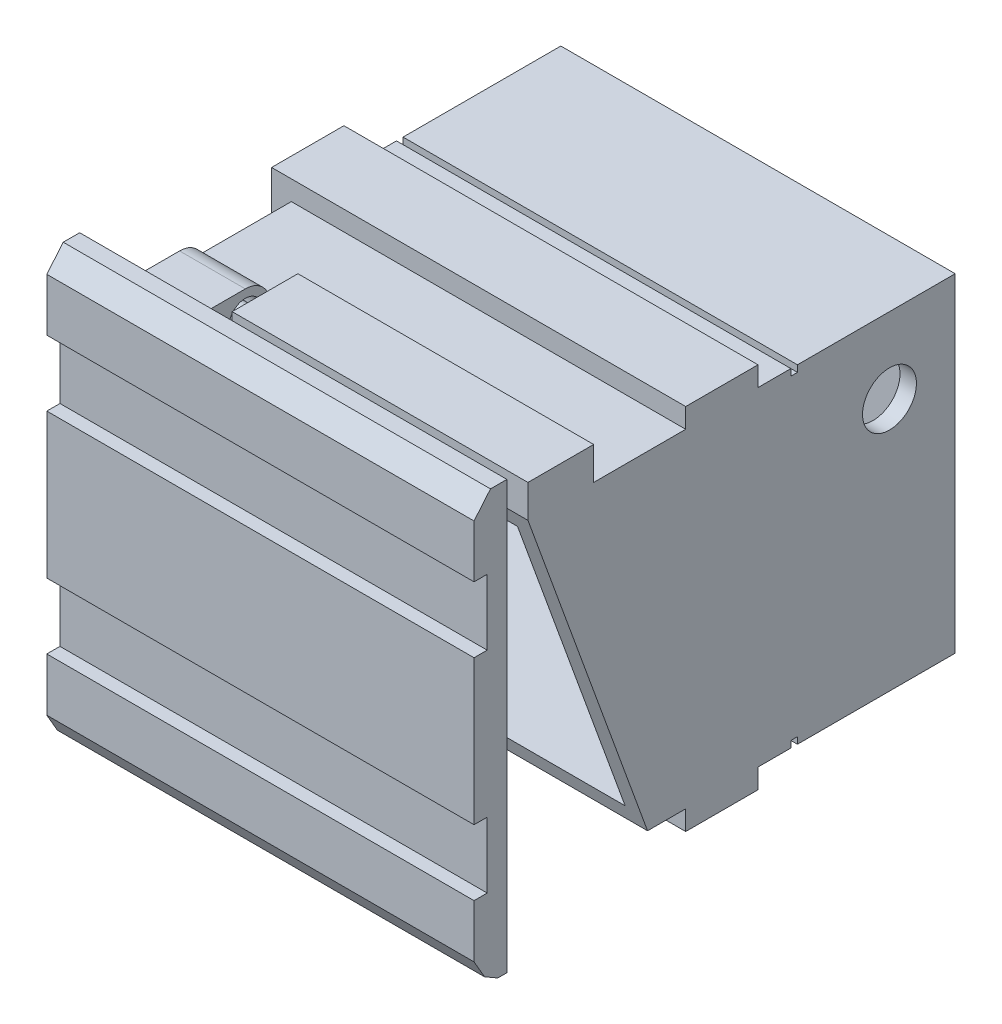
SolidWorks part; units mm, degrees
ref_plane "Alzado" through (0, 0, 0) normal (0, 0, 1) x (1, 0, 0)
ref_plane "Planta" through (0, 0, 0) normal (0, 1, 0) x (1, 0, 0)
ref_plane "Vista lateral" through (0, 0, 0) normal (1, 0, 0) x (0, 0, -1)
sketch "Croquis2" plane through (0, 0, 0) normal (0, 0, 1) x (1, 0, 0)
  line L1 (-30, 25) -> (30, 25)
  line L2 (-30, 25) -> (-30, -25)
  line L3 (-30, -25) -> (30, -25)
  line L4 (30, 25) -> (30, -25)
  line L5 (-30, 25) -> (30, -25) construction
  line L6 (-30, -25) -> (30, 25) construction
  point P0 (0, 0)
  dimension "D1" = 60
  dimension "D2" = 50
extrude "Saliente-Extruir2" add sketch "Croquis2" along normal blind 5
sketch "Croquis3" plane through (0, 0, 5) normal (0, 0, 1) x (1, 0, 0)
  line L1 (-27.5, 22.5) -> (27.5, 22.5)
  line L2 (-27.5, 22.5) -> (-27.5, -22.5)
  line L3 (-27.5, -22.5) -> (27.5, -22.5)
  line L4 (27.5, 22.5) -> (27.5, -22.5)
  line L5 (-27.5, 22.5) -> (27.5, -22.5) construction
  line L6 (-27.5, -22.5) -> (27.5, 22.5) construction
  line L7 (30, -25) -> (-30, -25)
  line L8 (30, -25) -> (30, 25)
  line L9 (30, 25) -> (-30, 25)
  line L10 (-30, -25) -> (-30, 25)
  point P0 (0, 0)
  dimension "D1" = 55
  dimension "D2" = 45
extrude "Saliente-Extruir3" add sketch "Croquis3" along normal blind 60
sketch "Croquis4" plane through (30, 0, 0) normal (1, 0, 0) x (0, 0, -1)
  line L0 (0, -25) -> (0, 25) construction
  line L2 (-65, 25) -> (0, 25) construction
  line L3 (-5, 22.5) -> (-15, 22.5)
  line L4 (-5, 22.5) -> (-5, 8.5)
  line L5 (-5, 8.5) -> (-15, 8.5)
  line L6 (-15, 22.5) -> (-15, 8.5)
  circle A1 centre (-10, 13.5) radius 4.1
  dimension "D1" = 14
  dimension "D2" = 5
  dimension "D3" = 8.2
  dimension "D4" = 5
  dimension "D5" = 5
  dimension "D6" = 2.5
  dimension "D7" = 10
extrude "Cortar-Extruir2" cut sketch "Croquis4" against normal blind 5 contours A1
sketch "Croquis5" plane through (30, 0, 0) normal (1, 0, 0) x (0, 0, -1)
  line L0 (-65, 25) -> (-46.8015, -25)
  line L1 (-65, -25) -> (0, -25) construction
  line L2 (-65, -25) -> (-65, 25) construction
  line L3 (-46.8015, -25) -> (-65, -25)
  line L4 (-65, -25) -> (-65, 25)
  dimension "D1" = 20
extrude "Cortar-Extruir3" cut sketch "Croquis5" against normal through all
sketch "Croquis18" plane through (-30, 0, 0) normal (-1, 0, 0) x (0, 0, 1)
  line L0 (65, 25) -> (0, 25) construction
  line L1 (46.8015, -25) -> (0, -25) construction
  line L2 (30, 25) -> (41, 25)
  line L3 (30, 25) -> (30, -25)
  line L4 (30, -25) -> (41, -25)
  line L5 (41, 25) -> (41, -25)
  line L6 (0, 25) -> (0, -25) construction
  dimension "D1" = 30
  dimension "11" = 11
extrude "Saliente-Extruir10" add sketch "Croquis18" along normal blind 3
sketch "Croquis19" plane through (0, -25, 0) normal (0, -1, 0) x (1, 0, 0)
  line L0 (30, 46.8015) -> (30, 0) construction
  line L2 (-33, 41) -> (30, 41)
  line L3 (-33, 41) -> (-33, 30)
  line L4 (-33, 30) -> (30, 30)
  line L5 (30, 41) -> (30, 30)
  dimension "D1" = 11
extrude "Saliente-Extruir11" add sketch "Croquis19" along normal blind 3
sketch "Croquis20" plane through (0, 25, 0) normal (0, 1, 0) x (1, 0, 0)
  line L1 (-33, -41) -> (30, -41)
  line L2 (-33, -41) -> (-33, -30)
  line L3 (-33, -30) -> (30, -30)
  line L4 (30, -41) -> (30, -30)
extrude "Saliente-Extruir12" add sketch "Croquis20" along normal blind 3
sketch "Croquis21" plane through (30, 0, 0) normal (1, 0, 0) x (0, 0, -1)
  line L0 (-30, -25) -> (0, -25) construction
  line L1 (-25, -25) -> (-24, -25)
  line L2 (-25, -25) -> (-25, -24)
  line L3 (-25, -24) -> (-24, -24)
  line L4 (-24, -25) -> (-24, -24)
  line L5 (-30, -28) -> (-30, -25) construction
  dimension "D1" = 5
  dimension "D2" = 1
  dimension "1" = 1
extrude "Cortar-Extruir8" cut sketch "Croquis21" against normal blind 65
sketch "Croquis23" plane through (30, 0, 0) normal (1, 0, 0) x (0, 0, -1)
  line L0 (-30, 25) -> (0, 25) construction
  line L1 (-25, 25) -> (-24, 25)
  line L2 (-25, 25) -> (-25, 24)
  line L3 (-25, 24) -> (-24, 24)
  line L4 (-24, 25) -> (-24, 24)
  line L5 (-30, 28) -> (-30, 25) construction
  dimension "D1" = 5
  dimension "D2" = 1
  dimension "D3" = 1
extrude "Cortar-Extruir10" cut sketch "Croquis23" against normal blind 65
sketch "Croquis22" plane through (0, 25, 0) normal (0, 1, 0) x (1, 0, 0)
  line L0 (-30, -30) -> (-30, -25) construction
  line L1 (-30, -25) -> (-29, -25)
  line L2 (-30, -25) -> (-30, -24)
  line L3 (-30, -24) -> (-29, -24)
  line L4 (-29, -25) -> (-29, -24)
  line L5 (30, -30) -> (-30, -30) construction
  dimension "D1" = 1
  dimension "D2" = 1
  dimension "5" = 5
extrude "Cortar-Extruir9" cut sketch "Croquis22" against normal blind 65
sketch "Croquis29" plane through (0, 25, 0) normal (0, 1, 0) x (1, 0, 0)
  line L0 (30, -65) -> (30, -41) construction
  line L1 (30, -55) -> (-15, -55)
  line L2 (30, -55) -> (30, -65)
  line L3 (30, -65) -> (-15, -65)
  line L4 (-15, -55) -> (-15, -65)
  line L5 (30, -65) -> (-30, -65) construction
  dimension "D1" = 45
  dimension "D2" = 10
extrude "Saliente-Extruir13" add sketch "Croquis29" along normal blind 5
sketch "Croquis30" plane through (0, 25, 0) normal (0, 1, 0) x (1, 0, 0)
  line L0 (-15, -65) -> (-30, -65) construction
  line L1 (-15, -55) -> (-27.5, -55)
  line L2 (-15, -55) -> (-15, -65)
  line L3 (-15, -65) -> (-27.5, -65)
  line L4 (-27.5, -55) -> (-27.5, -65)
  line L5 (-30, -65) -> (-30, -41) construction
  dimension "D1" = 2.5
extrude "Cortar-Extruir11" cut sketch "Croquis30" against normal blind 3
sketch "Croquis31" plane through (-15, 0, 0) normal (-1, 0, 0) x (0, 0, 1)
  line L0 (55, 30) -> (65, 30) construction
  line L2 (55, 30) -> (55, 25) construction
  circle A0 centre (61, 26.25) radius 1.5
  dimension "D2" = 3
  dimension "D1" = 3.75
  dimension "D3" = 6
extrude "Saliente-Extruir14" add sketch "Croquis31" along normal blind 11.5
sketch "Croquis32" plane through (-15, 0, 0) normal (-1, 0, 0) x (0, 0, 1)
  line L0 (61, 30) -> (68.2, 30)
  line L1 (68.2, 30) -> (68.2, 22.5)
  line L2 (61, 22.5) -> (68.2, 22.5)
  circle A1 centre (61, 26.25) radius 2.5
  arc A4 (61, 30) -> (61, 22.5) centre (61, 26.25) ccw
  dimension "D1" = 1.25
  dimension "D2" = 7.5
  dimension "D3" = 7.2
extrude "Saliente-Extruir15" add sketch "Croquis32" along normal blind 12
sketch "Croquis33" plane through (-15, 0, 0) normal (-1, 0, 0) x (0, 0, 1)
  line L1 (55, 22.5) -> (70, 22.5)
  line L2 (55, 22.5) -> (55, 31.9624)
  line L3 (55, 31.9624) -> (70, 31.9624)
  line L4 (70, 22.5) -> (70, 31.9624)
  circle A0 centre (61, 26.25) radius 1.5
  dimension "D3" = 3
  dimension "D1" = 15
  dimension "D2" = 9.4624
extrude "Cortar-Extruir12" cut sketch "Croquis33" along normal blind 2
sketch "Croquis34" plane through (0, 0, 68.2) normal (0, 0, 1) x (1, 0, 0)
  line L0 (30, -25) -> (30, 25) construction
  line L1 (30, 32) -> (-35, 32)
  line L2 (30, 32) -> (30, -33)
  line L3 (30, -33) -> (-35, -33)
  line L4 (-35, 32) -> (-35, -33)
  line L5 (-15, 30) -> (30, 30) construction
  dimension "D1" = 65
  dimension "D2" = 65
  dimension "D3" = 2
extrude "Saliente-Extruir16" add sketch "Croquis34" along normal blind 5
ref_plane "Plano1" through (30, 32, 73.2) normal (0, 0, -1) x (-1, 0, 0)
sketch "Croquis36" plane through (30, 0, 0) normal (1, 0, 0) x (0, 0, -1)
  line L0 (-70.7, 32) -> (-73.2, 29.0206)
  line L1 (-73.2, 32) -> (-68.2, 32) construction
  line L2 (-73.2, -33) -> (-73.2, 32) construction
  line L3 (-68.2, -33) -> (-68.2, 32) construction
  line L4 (-73.2, 29.0206) -> (-73.2, 32)
  line L5 (-73.2, 30.625) -> (-73.2, 33.375) construction
  line L6 (-73.2, 32) -> (-70.7, 32)
  dimension "D1" = 40
extrude "Cortar-Extruir13" cut sketch "Croquis36" against normal blind 65
sketch "Croquis37" plane through (30, 0, 0) normal (1, 0, 0) x (0, 0, -1)
  line L0 (-73.2, -33) -> (-68.2, -33) construction
  line L1 (-69.5895, -33) -> (-71.6017, -31.8383)
  line L2 (-71.6017, -31.8383) -> (-73.2, -29.0699)
  line L3 (-73.2, -33) -> (-73.2, 29.0206) construction
  line L4 (-68.2, -33) -> (-68.2, 32) construction
  line L5 (-69.5895, -33) -> (-73.2, -33)
  line L6 (-73.2, -33) -> (-73.2, -29.0699)
  dimension "D1" = 60
  dimension "D2" = 2.7684
  dimension "30" = 30
  dimension "D3" = 3.6105
extrude "Cortar-Extruir14" cut sketch "Croquis37" against normal blind 65 contours L6 L2 L1 L5
sketch "Croquis38" plane through (-35, 0, 0) normal (-1, 0, 0) x (0, 0, 1)
  line L0 (73.2, 29.0206) -> (73.2, -29.0699) construction
  line L1 (73.2, -21) -> (71.2, -21)
  line L2 (71.2, -21) -> (71.2, -11)
  line L3 (71.2, -11) -> (73.2, -11)
  line L4 (73.2, -11) -> (73.2, -21)
  line L5 (69.5895, -33) -> (68.2, -33) construction
  line L6 (68.2, 0) -> (73.5407, 0) construction
  line L7 (68.2, 32) -> (68.2, -33) construction
  line L8 (71.2, 11) -> (73.2, 11)
  line L9 (71.2, 21) -> (71.2, 11)
  line L10 (73.2, 21) -> (71.2, 21)
  line L11 (73.2, 11) -> (73.2, 21)
  dimension "D1" = 2
  dimension "D2" = 10
  dimension "12" = 12
extrude "Cortar-Extruir15" cut sketch "Croquis38" against normal blind 65
